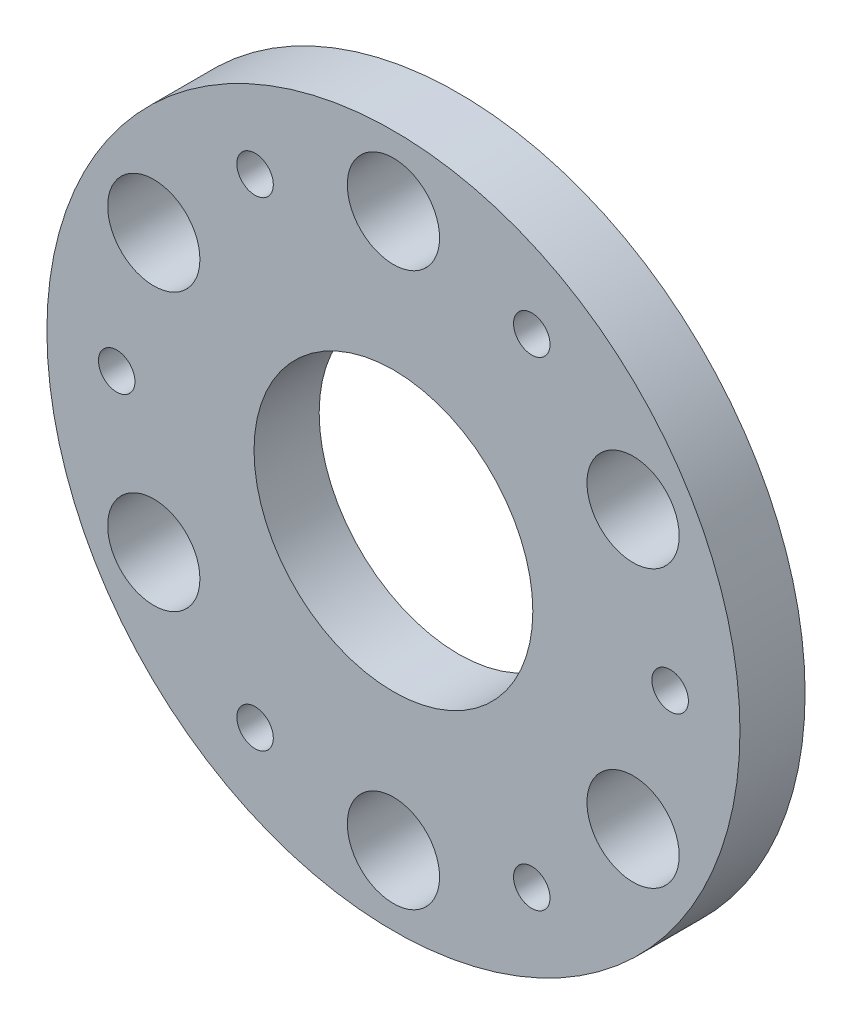
SolidWorks part; units mm, degrees
material "6061-T6 (SS)"
ref_plane "Front Plane" through (0, 0, 0) normal (0, 0, 1) x (1, 0, 0)
ref_plane "Top Plane" through (0, 0, 0) normal (0, 1, 0) x (1, 0, 0)
ref_plane "Right Plane" through (0, 0, 0) normal (1, 0, 0) x (0, 0, -1)
sketch "Sketch1" plane through (0, 0, 0) normal (0, 0, 1) x (1, 0, 0)
  line L0 (0, 0) -> (0, -13.4874) construction
  circle A0 centre (0, 0) radius 16.891
  circle A2 centre (0, -13.4874) radius 2.2479
  circle A3 centre (-11.6804, -6.7437) radius 2.2479
  circle A4 centre (-11.6804, 6.7437) radius 2.2479
  circle A5 centre (0, 13.4874) radius 2.2479
  circle A6 centre (11.6804, 6.7437) radius 2.2479
  circle A7 centre (11.6804, -6.7437) radius 2.2479
  dimension "D1" = 33.782
  dimension "D2" = 4.4958
  dimension "D3" = 6
extrude "Boss-Extrude1" add sketch "Sketch1" along normal blind 3.175
hole_wizard "Tap Drill for #4-40 Tap1" positions "Sketch5" profile "Sketch6" hole size "#4-40" standard "ANSI Inch" end condition through all
sketch "Sketch5" plane through (0, 0, 3.175) normal (0, 0, 1) x (1, 0, 0)
  point P0 (0, 0)
sketch "Sketch6" plane through (0, 0, 3.175) normal (1, 0, 0) x (0, -1, 0)
  line L0 (0, 0) -> (0, 3.175)
  line L1 (0, 3.175) -> (6.7945, 3.175)
  line L2 (6.7945, 3.175) -> (6.7945, 0)
  line L5 (6.7945, 0) -> (0, 0)
  line L11 (0, -6.35) -> (0, 107.95) construction
  dimension "Thru Hole Dia." = 13.589
  dimension "Thru Hole Depth" = 3.175
sketch "Sketch7" plane through (0, 0, 3.175) normal (0, 0, 1) x (1, 0, 0)
  line L0 (0, 0) -> (11.6804, -6.7437) construction
  line L1 (0, 0) -> (13.4874, 0) construction
  circle A0 centre (0, 0) radius 13.4874
  dimension "D1" = 26.9748
hole_wizard "Tap Drill for #2-56 Tap1" positions "Sketch8" profile "Sketch9" hole size "#2-56" standard "ANSI Inch" end condition through all
sketch "Sketch8" plane through (0, 0, 3.175) normal (0, 0, 1) x (1, 0, 0)
  point P0 (13.4874, 0)
sketch "Sketch9" plane through (13.4874, 0, 3.175) normal (1, 0, 0) x (0, -1, 0)
  line L0 (0, 0) -> (0, 3.175)
  line L1 (0, 3.175) -> (0.889, 3.175)
  line L2 (0.889, 3.175) -> (0.889, 0)
  line L5 (0.889, 0) -> (0, 0)
  line L11 (0, -6.35) -> (0, 107.95) construction
  dimension "Thru Hole Dia." = 1.778
  dimension "Thru Hole Depth" = 3.175
pattern_circular "CirPattern1" count 6 over 360 about axis through (0, 0, 0) along (0, 0, 1) of "Tap Drill for #2-56 Tap1"
